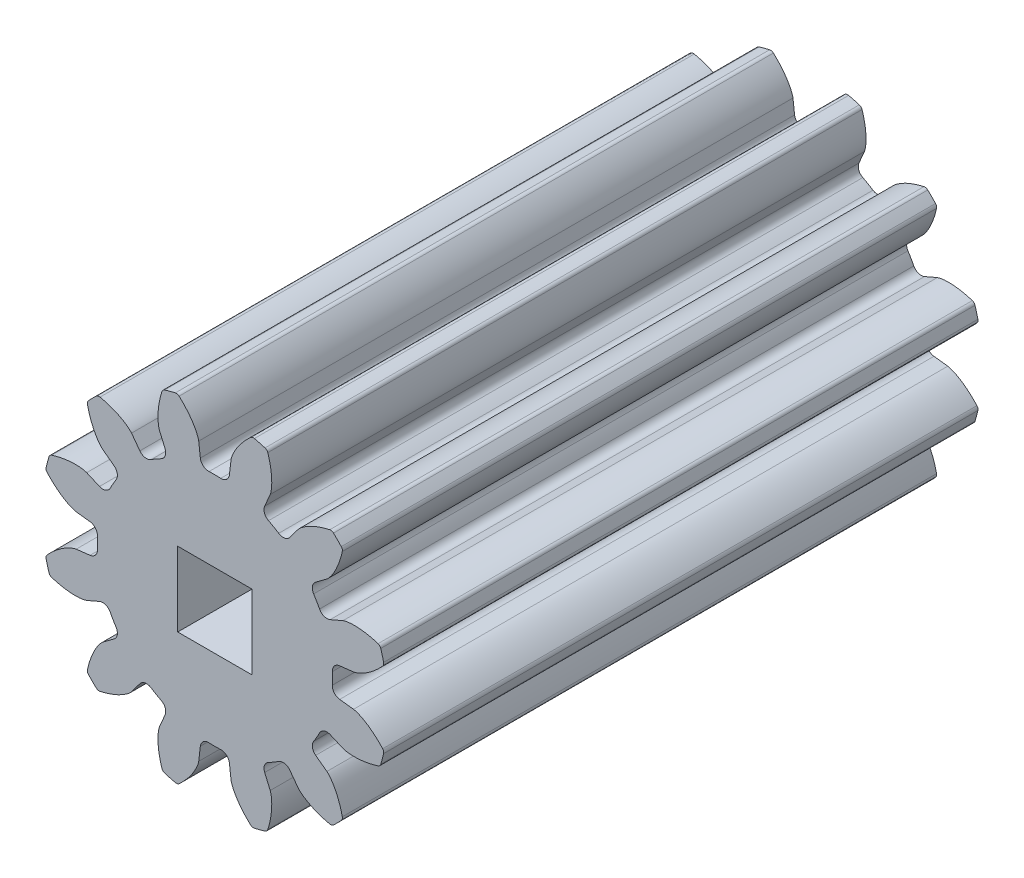
SolidWorks part; units mm, degrees
material "ABS"
ref_plane "Front" through (0, 0, 0) normal (0, 0, 1) x (1, 0, 0)
ref_plane "Top" through (0, 0, 0) normal (0, 1, 0) x (1, 0, 0)
ref_plane "Right" through (0, 0, 0) normal (1, 0, 0) x (0, 0, -1)
sketch "Sketch1" plane through (0, 0, 0) normal (0, 0, 1) x (1, 0, 0)
  circle A0 centre (0, 0) radius 7.4083
extrude "Boss-Extrude1" add sketch "Sketch1" along normal blind 25.4
sketch "Sketch3" plane through (0, 0, 0) normal (0, 0, 1) x (1, 0, 0)
  line L0 (0, 0) -> (43.7181, 0) construction
  line L2 (0, 0) -> (-0.5818, 4.9933) construction
  line L3 (0, 0) -> (0.5818, 4.9933) construction
  line L4 (0.5818, 4.9933) -> (0.6906, 5.927) construction
  line L5 (0, 0) -> (0, 61.276) construction
  line L6 (-0.5818, 4.9933) -> (-0.6906, 5.927) construction
  circle A0 centre (0, 0) radius 7.4083 construction
  circle A1 centre (0, 0) radius 6.35 construction
  circle A2 centre (0, 0) radius 5.967 construction
  arc A3 (0.5818, 4.9933) -> (-0.5818, 4.9933) centre (0, 0) ccw construction
  arc A5 (1.5983, 7.2339) -> (-1.5983, 7.2339) centre (0, 0) ccw
  spline S0 degree 4 poles (-0.6906, 5.927) (-0.6909, 5.9293) (-0.6919, 5.9359) (-0.6942, 5.9484) (-0.6987, 5.9686) (-0.7052, 5.9942) (-0.7148, 6.0271) (-0.7275, 6.0655) (-0.7428, 6.1073) (-0.761, 6.1523) (-0.7804, 6.1969) (-0.8011, 6.2409) (-0.8228, 6.2844) (-0.8503, 6.3367) (-0.8852, 6.3986) (-0.9285, 6.47) (-0.9807, 6.5497) (-1.0371, 6.6294) (-1.0952, 6.7066) (-1.1568, 6.7832) (-1.2185, 6.8562) (-1.2856, 6.9304) (-1.3489, 6.9981) (-1.4232, 7.0721) (-1.484, 7.1312) (-1.5675, 7.2071) (-1.6179, 7.2513) (-1.6779, 7.3023) (-1.7051, 7.3245) (-1.7219, 7.3382) knots 0 0 0 0 0 0.005377 0.015084 0.028532 0.04661 0.064855 0.092111 0.119476 0.146842 0.174209 0.201575 0.228941 0.256307 0.307035 0.361767 0.4165 0.471232 0.525964 0.580697 0.635429 0.690161 0.744894 0.799626 0.854358 0.909091 0.954545 1 1 1 1 1 construction
  spline S1 degree 4 poles (-0.6906, 5.927) (-0.6909, 5.9293) (-0.6919, 5.9359) (-0.6942, 5.9484) (-0.6987, 5.9686) (-0.7052, 5.9942) (-0.7148, 6.0271) (-0.7275, 6.0655) (-0.7428, 6.1073) (-0.761, 6.1523) (-0.7804, 6.1969) (-0.8011, 6.2409) (-0.8228, 6.2844) (-0.8503, 6.3367) (-0.8852, 6.3986) (-0.9285, 6.47) (-0.9807, 6.5497) (-1.0371, 6.6294) (-1.0952, 6.7066) (-1.1568, 6.7832) (-1.2185, 6.8562) (-1.2856, 6.9304) (-1.3489, 6.9981) (-1.4232, 7.0721) (-1.484, 7.1312) (-1.5494, 7.1906) (-1.5816, 7.2193) (-1.5983, 7.2339) knots 0 0 0 0 0 0.005377 0.015084 0.028532 0.04661 0.064855 0.092111 0.119476 0.146842 0.174209 0.201575 0.228941 0.256307 0.307035 0.361767 0.4165 0.471232 0.525964 0.580697 0.635429 0.690161 0.744894 0.799626 0.854358 0.909091 0.909091 0.909091 0.909091 0.909091
  spline S2 degree 4 poles (0.6906, 5.927) (0.6909, 5.9293) (0.6919, 5.9359) (0.6942, 5.9484) (0.6987, 5.9686) (0.7052, 5.9942) (0.7148, 6.0271) (0.7275, 6.0655) (0.7428, 6.1073) (0.761, 6.1523) (0.7804, 6.1969) (0.8011, 6.2409) (0.8228, 6.2844) (0.8503, 6.3367) (0.8852, 6.3986) (0.9285, 6.47) (0.9807, 6.5497) (1.0371, 6.6294) (1.0952, 6.7066) (1.1568, 6.7832) (1.2185, 6.8562) (1.2856, 6.9304) (1.3489, 6.9981) (1.4232, 7.0721) (1.484, 7.1312) (1.5675, 7.2071) (1.6179, 7.2513) (1.6779, 7.3023) (1.7051, 7.3245) (1.7219, 7.3382) knots 0 0 0 0 0 0.005377 0.015084 0.028532 0.04661 0.064855 0.092111 0.119476 0.146842 0.174209 0.201575 0.228941 0.256307 0.307035 0.361767 0.4165 0.471232 0.525964 0.580697 0.635429 0.690161 0.744894 0.799626 0.854358 0.909091 0.954545 1 1 1 1 1 construction
  spline S3 degree 4 poles (0.6906, 5.927) (0.6909, 5.9293) (0.6919, 5.9359) (0.6942, 5.9484) (0.6987, 5.9686) (0.7052, 5.9942) (0.7148, 6.0271) (0.7275, 6.0655) (0.7428, 6.1073) (0.761, 6.1523) (0.7804, 6.1969) (0.8011, 6.2409) (0.8228, 6.2844) (0.8503, 6.3367) (0.8852, 6.3986) (0.9285, 6.47) (0.9807, 6.5497) (1.0371, 6.6294) (1.0952, 6.7066) (1.1568, 6.7832) (1.2185, 6.8562) (1.2856, 6.9304) (1.3489, 6.9981) (1.4232, 7.0721) (1.484, 7.1312) (1.5494, 7.1906) (1.5816, 7.2193) (1.5983, 7.2339) knots 0 0 0 0 0 0.005377 0.015084 0.028532 0.04661 0.064855 0.092111 0.119476 0.146842 0.174209 0.201575 0.228941 0.256307 0.307035 0.361767 0.4165 0.471232 0.525964 0.580697 0.635429 0.690161 0.744894 0.799626 0.854358 0.909091 0.909091 0.909091 0.909091 0.909091
  point P0 (0, 5.0271)
sketch "DCLTBC" plane through (0, 0, 0) normal (0, 0, 1) x (1, 0, 0)
  line L0 (0, 0) -> (41.04, 0) construction
  line L1 (-0.5818, 4.9933) -> (-0.6906, 5.927) construction
  line L2 (0.5818, 4.9933) -> (0.6906, 5.927) construction
  line L3 (-0.5818, 4.9933) -> (-0.6906, 5.927)
  line L4 (0.5818, 4.9933) -> (0.6906, 5.927)
  line L5 (0, 0) -> (0, 104.9356) construction
  circle A0 centre (0, 0) radius 7.4083
  circle A1 centre (0, 0) radius 6.35 construction
  circle A2 centre (0, 0) radius 5.967 construction
  arc A3 (0.5818, 4.9933) -> (-0.5818, 4.9933) centre (0, 0) ccw construction
  arc A4 (0.5818, 4.9933) -> (-0.5818, 4.9933) centre (0, 0) ccw
  spline S0 degree 4 poles (-992.2327, -123.7493) (-11.7184, 3.7577) (-0.7821, 5.3359) (-0.6334, 5.6707) (-0.6987, 5.9686) (-0.7052, 5.9942) (-0.7148, 6.0271) (-0.7275, 6.0655) (-0.7428, 6.1073) (-0.761, 6.1523) (-0.7804, 6.1969) (-0.8011, 6.2409) (-0.8228, 6.2844) (-0.8503, 6.3367) (-0.8852, 6.3986) (-0.9285, 6.47) (-0.9807, 6.5497) (-1.0371, 6.6294) (-1.0952, 6.7066) (-1.1568, 6.7832) (-1.2185, 6.8562) (-1.2856, 6.9304) (-1.3489, 6.9981) (-1.4232, 7.0721) (-1.7629, 7.4024) (-3.091, 8.4823) (16.0015, -8.3782) (-754.2601, 665.5952) knots -0.639841 -0.639841 -0.639841 -0.639841 -0.639841 0.005377 0.015084 0.028532 0.04661 0.064855 0.092111 0.119476 0.146842 0.174209 0.201575 0.228941 0.256307 0.307035 0.361767 0.4165 0.471232 0.525964 0.580697 0.635429 0.690161 0.744894 0.799626 0.854358 1.913215 1.913215 1.913215 1.913215 1.913215 only from (-0.6906, 5.927) to (-1.5983, 7.2339) construction
  spline S1 degree 4 poles (992.2327, -123.7493) (11.7184, 3.7577) (0.7821, 5.3359) (0.6334, 5.6707) (0.6987, 5.9686) (0.7052, 5.9942) (0.7148, 6.0271) (0.7275, 6.0655) (0.7428, 6.1073) (0.761, 6.1523) (0.7804, 6.1969) (0.8011, 6.2409) (0.8228, 6.2844) (0.8503, 6.3367) (0.8852, 6.3986) (0.9285, 6.47) (0.9807, 6.5497) (1.0371, 6.6294) (1.0952, 6.7066) (1.1568, 6.7832) (1.2185, 6.8562) (1.2856, 6.9304) (1.3489, 6.9981) (1.4232, 7.0721) (1.7629, 7.4024) (3.091, 8.4823) (-16.0015, -8.3782) (754.2601, 665.5952) knots -0.639841 -0.639841 -0.639841 -0.639841 -0.639841 0.005377 0.015084 0.028532 0.04661 0.064855 0.092111 0.119476 0.146842 0.174209 0.201575 0.228941 0.256307 0.307035 0.361767 0.4165 0.471232 0.525964 0.580697 0.635429 0.690161 0.744894 0.799626 0.854358 1.913215 1.913215 1.913215 1.913215 1.913215 only from (0.6906, 5.927) to (1.5983, 7.2339) construction
  spline S2 degree 4 poles (-0.6906, 5.927) (-0.6909, 5.9293) (-0.6919, 5.9359) (-0.6942, 5.9484) (-0.6987, 5.9686) (-0.7052, 5.9942) (-0.7148, 6.0271) (-0.7275, 6.0655) (-0.7428, 6.1073) (-0.761, 6.1523) (-0.7804, 6.1969) (-0.8011, 6.2409) (-0.8228, 6.2844) (-0.8503, 6.3367) (-0.8852, 6.3986) (-0.9285, 6.47) (-0.9807, 6.5497) (-1.0371, 6.6294) (-1.0952, 6.7066) (-1.1568, 6.7832) (-1.2185, 6.8562) (-1.2856, 6.9304) (-1.3489, 6.9981) (-1.4232, 7.0721) (-1.484, 7.1312) (-1.5494, 7.1906) (-1.5816, 7.2193) (-1.5983, 7.2339) knots 0 0 0 0 0 0.005377 0.015084 0.028532 0.04661 0.064855 0.092111 0.119476 0.146842 0.174209 0.201575 0.228941 0.256307 0.307035 0.361767 0.4165 0.471232 0.525964 0.580697 0.635429 0.690161 0.744894 0.799626 0.854358 0.909091 0.909091 0.909091 0.909091 0.909091
  spline S3 degree 4 poles (0.6906, 5.927) (0.6909, 5.9293) (0.6919, 5.9359) (0.6942, 5.9484) (0.6987, 5.9686) (0.7052, 5.9942) (0.7148, 6.0271) (0.7275, 6.0655) (0.7428, 6.1073) (0.761, 6.1523) (0.7804, 6.1969) (0.8011, 6.2409) (0.8228, 6.2844) (0.8503, 6.3367) (0.8852, 6.3986) (0.9285, 6.47) (0.9807, 6.5497) (1.0371, 6.6294) (1.0952, 6.7066) (1.1568, 6.7832) (1.2185, 6.8562) (1.2856, 6.9304) (1.3489, 6.9981) (1.4232, 7.0721) (1.484, 7.1312) (1.5494, 7.1906) (1.5816, 7.2193) (1.5983, 7.2339) knots 0 0 0 0 0 0.005377 0.015084 0.028532 0.04661 0.064855 0.092111 0.119476 0.146842 0.174209 0.201575 0.228941 0.256307 0.307035 0.361767 0.4165 0.471232 0.525964 0.580697 0.635429 0.690161 0.744894 0.799626 0.854358 0.909091 0.909091 0.909091 0.909091 0.909091
extrude "Cut-Extrude-DCLTBC" cut sketch "DCLTBC" along normal through all
fillet "Fillet-Tip-DCLTBC" radius 0.1775 2 edges at (1.5983, 7.2339, 12.7) (-1.5983, 7.2339, 12.7)
fillet "Fillet-Root-DCLTBC" radius 0.3551 2 edges at (-0.5818, 4.9933, 12.7) (0.5818, 4.9933, 12.7)
pattern_circular "CirPattern-DCLTBC" count 12 over 360 about axis through (0, 0, 25.4) along (0, 0, 1) of "Cut-Extrude-DCLTBC", "Fillet-Tip-DCLTBC", "Fillet-Root-DCLTBC"
sketch "DCGTBC" [suppressed] plane through (0, 0, 0) normal (0, 0, 1) x (1, 0, 0)
  line L0 (0, 0) -> (41.04, 0) construction
  line L1 (-33.4742, 2.9286) -> (0, 0) construction
  line L2 (0, 0) -> (33.4742, 2.9286) construction
  line L3 (0, 0) -> (-16.5124, 0)
  line L5 (0, 0) -> (0, 104.9356) construction
  circle A0 centre (0, 0) radius 35.9833
  circle A1 centre (0, 0) radius 34.925 construction
  circle A2 centre (0, 0) radius 32.8188 construction
  arc A3 (0.2989, 33.6008) -> (-0.2989, 33.6008) centre (0, 0) ccw construction
  arc A11 (33.4742, 2.9286) -> (-33.4742, 2.9286) centre (0, 0) ccw
  spline S4 degree 4 poles (999.6179, -3.7707) (12.1623, 31.0827) (0.4581, 31.7209) (0.2553, 32.3127) (0.2967, 32.9045) (0.3017, 32.9586) (0.3095, 33.0284) (0.3204, 33.1106) (0.3343, 33.201) (0.3514, 33.2993) (0.3703, 33.3974) (0.3907, 33.4951) (0.4126, 33.5925) (0.4408, 33.7105) (0.477, 33.8518) (0.523, 34.017) (0.5794, 34.2042) (0.6413, 34.395) (0.706, 34.5826) (0.7756, 34.772) (0.846, 34.9552) (0.9235, 35.1454) (0.9973, 35.3209) (1.0848, 35.5175) (1.4313, 36.2799) (2.6636, 38.6565) (-10.9768, 10.7922) (444.1484, 932.5353) knots -0.603811 -0.603811 -0.603811 -0.603811 -0.603811 0.005377 0.015084 0.028532 0.04661 0.064855 0.092111 0.119476 0.146842 0.174209 0.201575 0.228941 0.256307 0.307035 0.361767 0.4165 0.471232 0.525964 0.580697 0.635429 0.690161 0.744894 0.799626 0.854358 1.742885 1.742885 1.742885 1.742885 1.742885 only from (0.2919, 32.8175) to (1.2943, 35.96) construction
  spline S5 degree 4 poles (-999.6179, -3.7707) (-12.1623, 31.0827) (-0.4581, 31.7209) (-0.2553, 32.3127) (-0.2967, 32.9045) (-0.3017, 32.9586) (-0.3095, 33.0284) (-0.3204, 33.1106) (-0.3343, 33.201) (-0.3514, 33.2993) (-0.3703, 33.3974) (-0.3907, 33.4951) (-0.4126, 33.5925) (-0.4408, 33.7105) (-0.477, 33.8518) (-0.523, 34.017) (-0.5794, 34.2042) (-0.6413, 34.395) (-0.706, 34.5826) (-0.7756, 34.772) (-0.846, 34.9552) (-0.9235, 35.1454) (-0.9973, 35.3209) (-1.0848, 35.5175) (-1.4313, 36.2799) (-2.6636, 38.6565) (10.9768, 10.7922) (-444.1484, 932.5353) knots -0.603811 -0.603811 -0.603811 -0.603811 -0.603811 0.005377 0.015084 0.028532 0.04661 0.064855 0.092111 0.119476 0.146842 0.174209 0.201575 0.228941 0.256307 0.307035 0.361767 0.4165 0.471232 0.525964 0.580697 0.635429 0.690161 0.744894 0.799626 0.854358 1.742885 1.742885 1.742885 1.742885 1.742885 only from (-0.2919, 32.8175) to (-1.2943, 35.96) construction
  spline S6 degree 4 poles (0.2919, 32.8175) (0.292, 32.8224) (0.2924, 32.8361) (0.2937, 32.8621) (0.2967, 32.9045) (0.3017, 32.9586) (0.3095, 33.0284) (0.3204, 33.1106) (0.3343, 33.201) (0.3514, 33.2993) (0.3703, 33.3974) (0.3907, 33.4951) (0.4126, 33.5925) (0.4408, 33.7105) (0.477, 33.8518) (0.523, 34.017) (0.5794, 34.2042) (0.6413, 34.395) (0.706, 34.5826) (0.7756, 34.772) (0.846, 34.9552) (0.9235, 35.1454) (0.9973, 35.3209) (1.0848, 35.5175) (1.1568, 35.676) (1.2354, 35.8397) (1.2742, 35.9193) (1.2943, 35.96) knots 0 0 0 0 0 0.005377 0.015084 0.028532 0.04661 0.064855 0.092111 0.119476 0.146842 0.174209 0.201575 0.228941 0.256307 0.307035 0.361767 0.4165 0.471232 0.525964 0.580697 0.635429 0.690161 0.744894 0.799626 0.854358 0.909091 0.909091 0.909091 0.909091 0.909091
  spline S7 degree 4 poles (-0.2919, 32.8175) (-0.292, 32.8224) (-0.2924, 32.8361) (-0.2937, 32.8621) (-0.2967, 32.9045) (-0.3017, 32.9586) (-0.3095, 33.0284) (-0.3204, 33.1106) (-0.3343, 33.201) (-0.3514, 33.2993) (-0.3703, 33.3974) (-0.3907, 33.4951) (-0.4126, 33.5925) (-0.4408, 33.7105) (-0.477, 33.8518) (-0.523, 34.017) (-0.5794, 34.2042) (-0.6413, 34.395) (-0.706, 34.5826) (-0.7756, 34.772) (-0.846, 34.9552) (-0.9235, 35.1454) (-0.9973, 35.3209) (-1.0848, 35.5175) (-1.1568, 35.676) (-1.2354, 35.8397) (-1.2742, 35.9193) (-1.2943, 35.96) knots 0 0 0 0 0 0.005377 0.015084 0.028532 0.04661 0.064855 0.092111 0.119476 0.146842 0.174209 0.201575 0.228941 0.256307 0.307035 0.361767 0.4165 0.471232 0.525964 0.580697 0.635429 0.690161 0.744894 0.799626 0.854358 0.909091 0.909091 0.909091 0.909091 0.909091
  dimension "D1" = 5
  dimension "D2" = 5
extrude "Cut-Extrude-DCGTBC" [suppressed] cut sketch "DCGTBC" along normal through all
fillet "Fillet-Tip-DCGTBC" [suppressed] radius 0.1775
pattern_circular "CirPattern-DCGTBC" [suppressed] count 12 over 360
sketch "Sketch4" plane through (0, 0, 25.4) normal (0, 0, 1) x (1, 0, 0)
  line L1 (-1.5875, -1.5875) -> (1.5875, -1.5875)
  line L2 (-1.5875, -1.5875) -> (-1.5875, 1.5875)
  line L3 (-1.5875, 1.5875) -> (1.5875, 1.5875)
  line L4 (1.5875, -1.5875) -> (1.5875, 1.5875)
  line L5 (-1.5875, -1.5875) -> (1.5875, 1.5875) construction
  line L6 (-1.5875, 1.5875) -> (1.5875, -1.5875) construction
  point P0 (0, 0)
  dimension "D1" = 3.175
extrude "Cut-Extrude2" cut sketch "Sketch4" against normal through all
equation "\"DiametralPitch\"= 24'Diametral Pitch"
equation "\"NumTeeth\"= 12'Number of Teeth"
equation "\"PressureAngle\"= 20deg'Pressure Angle"
equation "\"Addendum\"= 1 / \"DiametralPitch\"'Addendum"
equation "\"Dedendum\"= 1.25 / \"DiametralPitch\"'Dedendum"
equation "\"WorkingDepth\"= 2 / \"DiametralPitch\"'Working Depth - here for REF (Not used in building model)"
equation "\"WholeDepth\"= 2.25 / \"DiametralPitch\"'Whole Depth - here for REF (Not used in building model)"
equation "\"Clearance\"= .25 / \"DiametralPitch\"'Clearance"
equation "\"CircularPitch\"= pi / \"DiametralPitch\"'Circular Pitch - here for REF (Not used in building model)"
equation "\"PitchCircle\"= \"NumTeeth\" / \"DiametralPitch\"'Pitch Circle - or - Pitch Diameter"
equation "\"OutsideDiameter\"= ( \"NumTeeth\" + 2 ) / \"DiametralPitch\"'Outside Diameter"
equation "\"Fillet_Root\"= \"Clearance\" * cos ( \"PressureAngle\" ) * tan ( ( 90 + \"PressureAngle\" ) / 2 ) 'Fillet Root"
equation "\"AddendumCircle\"= \"PitchCircle\" + ( 2 * \"Addendum\" )'Addendum Circle - or - Addendum Diameter"
equation "\"DedendumCircle\"= \"PitchCircle\" - ( 2 * \"Dedendum\" )'Dedendum Circle - or - Dedendum Diameter"
equation "\"BaseCircle\"= \"PitchCircle\" * cos ( \"PressureAngle\" )'Base Circle - Base Diameter"
equation "\"PitchAngle\"= 360deg / \"NumTeeth\"'Pitch Angle"
equation "\"Alpha\"= sqr ( \"PitchCircle\" ^ 2 - \"BaseCircle\" ^ 2 ) / \"BaseCircle\" * 180 / PI - \"PressureAngle\"'Alpha - Used for Calculating Beta"
equation "\"Beta\"= ( \"PitchAngle\" / 4 - ( \"Alpha\" - 90 ) )'Beta - Used in definition of the parameters for the parametric equation driven curve"
equation "\"Gamma\"= ( \"PitchAngle\" / 4 - ( \"Alpha\" + 90 ) )'Gamma - Used in definition of the parameters for the parametric equation driven curve"
equation "\"Phi\"= sqr ( ( \"AddendumCircle\" / 2 ) ^ 2 - ( \"BaseCircle\" / 2 ) ^ 2 ) / ( \"BaseCircle\" / 2 )'Phi - Used in definition of the parameters for the parametric equation driven curve"
equation "\"DCGTBC\"= iif ( \"DedendumCircle\" > \"BaseCircle\" , \"unsuppressed\" , \"suppressed\" )'if Dedendum Circle IS GREATER THAN BaseCircle THEN UnsuppressORSuppress FEATURE"
equation "\"DCLTBC\"= iif ( \"DedendumCircle\" - .002 > \"BaseCircle\" , \"suppressed\" , \"unsuppressed\" )'if Dedendum Circle - .002 IS GREATER THAN BaseCircle THEN SuppressORUnsuppress FEATURE"
equation "\"Cut-Extrude-DCGTBC\"= iif ( \"DedendumCircle\" > \"BaseCircle\" , \"unsuppressed\" , \"suppressed\" )'if Dedendum Circle IS GREATER THAN BaseCircle THEN UnsuppressORSuppress FEATURE"
equation "\"Cut-Extrude-DCLTBC\"= iif ( \"DedendumCircle\" - .002 > \"BaseCircle\" , \"suppressed\" , \"unsuppressed\" )'if Dedendum Circle - .002 IS GREATER THAN BaseCircle THEN SuppressORUnsuppress FEATURE"
equation "\"CirPattern-DCGTBC\"= iif ( \"DedendumCircle\" > \"BaseCircle\" , \"unsuppressed\" , \"suppressed\" )'if Dedendum Circle IS GREATER THAN BaseCircle THEN UnsuppressORSuppress FEATURE"
equation "\"CirPattern-DCLTBC\"= iif ( \"DedendumCircle\" - .002 > \"BaseCircle\" , \"suppressed\" , \"unsuppressed\" )'if Dedendum Circle - .002 IS GREATER THAN BaseCircle THEN SuppressORUnsuppress FEATURE"
equation "\"Fillet-Tip-DCGTBC\"= iif ( \"DedendumCircle\" > \"BaseCircle\" , \"unsuppressed\" , \"suppressed\" )'if Dedendum Circle IS GREATER THAN BaseCircle THEN UnsuppressORSuppress FEATURE"
equation "\"Fillet-Tip-DCLTBC\"= iif ( \"DedendumCircle\" - .002 > \"BaseCircle\" , \"suppressed\" , \"unsuppressed\" )'if Dedendum Circle - .002 IS GREATER THAN BaseCircle THEN SuppressORUnsuppress FEATURE"
equation "\"Fillet-Root-DCLTBC\"= iif ( \"DedendumCircle\" - .002 > \"BaseCircle\" , \"suppressed\" , \"unsuppressed\" )'if Dedendum Circle - .002 IS GREATER THAN BaseCircle THEN SuppressORUnsuppress FEATURE"
equation "\"D1@CirPattern-DCGTBC\"= \"NumTeeth\"'Number of Teeth"
equation "\"D1@CirPattern-DCLTBC\"= \"NumTeeth\"'Number of Teeth"
equation "\"D1@Fillet-Tip-DCGTBC\"= \"Fillet_Root\" / 2 'Tip Rad For Large No of Teeth"
equation "\"D1@Fillet-Tip-DCLTBC\"=\"Fillet_Root\" / 2'Tip Rad For Small No of Teeth"
equation "\"D1@Fillet-Root-DCLTBC\"= \"Fillet_Root\"'Fillet Root"
